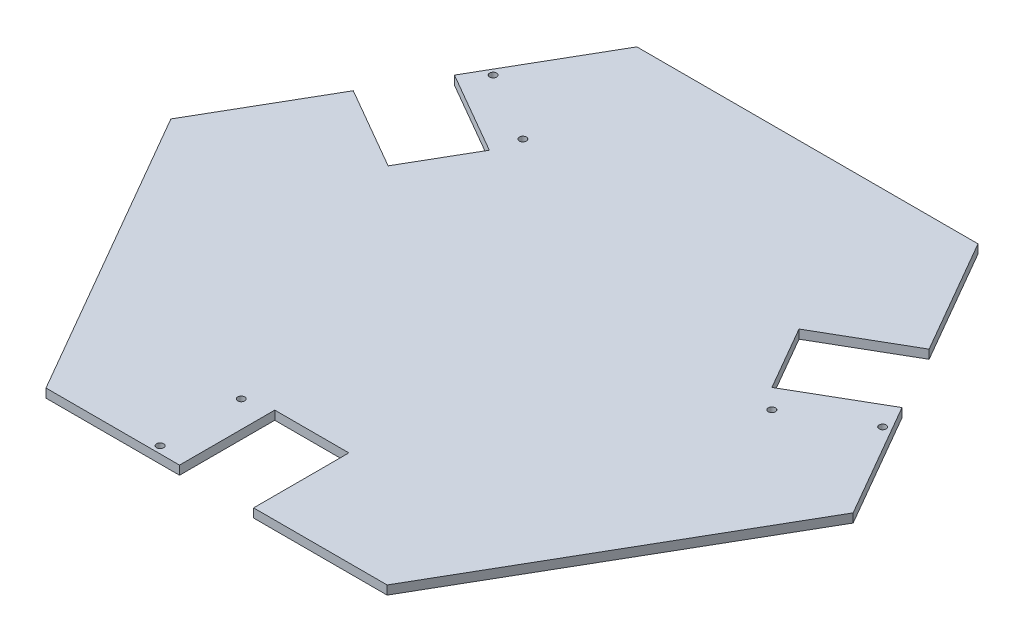
SolidWorks part; units mm, degrees
ref_plane "Front Plane" through (0, 0, 0) normal (0, 0, 1) x (1, 0, 0)
ref_plane "Top Plane" through (0, 0, 0) normal (0, 1, 0) x (1, 0, 0)
ref_plane "Right Plane" through (0, 0, 0) normal (1, 0, 0) x (0, 0, -1)
sketch "Sketch1" plane through (0, 0, 0) normal (0, 1, 0) x (1, 0, 0)
  line L0 (98.2939, 56.75) -> (0, 0) construction
  line L1 (-96.7062, 167.5) -> (-134.5593, 101.9365)
  line L2 (-96.7062, -167.5) -> (-21, -167.5)
  line L3 (193.4123, 0) -> (155.5593, 65.5635)
  line L4 (0, 0) -> (-145.0593, 83.75) construction
  line L5 (0, 0) -> (0, -167.5) construction
  line L6 (134.5593, 101.9365) -> (87.7939, 74.9365)
  line L7 (87.7939, 74.9365) -> (108.7939, 38.5635)
  line L8 (108.7939, 38.5635) -> (155.5593, 65.5635)
  line L9 (-108.7939, 38.5635) -> (-155.5593, 65.5635)
  line L10 (-87.7939, 74.9365) -> (-108.7939, 38.5635)
  line L11 (-134.5593, 101.9365) -> (-87.7939, 74.9365)
  line L12 (-21, -167.5) -> (-21, -113.5)
  line L13 (-21, -113.5) -> (21, -113.5)
  line L14 (21, -113.5) -> (21, -167.5)
  line L15 (-155.5593, 65.5635) -> (-193.4123, 0)
  line L16 (134.5593, 101.9365) -> (96.7062, 167.5)
  line L17 (21, -167.5) -> (96.7062, -167.5)
  line L18 (-96.7062, 167.5) -> (96.7062, 167.5)
  line L19 (96.7062, -167.5) -> (193.4123, 0)
  line L20 (-193.4123, 0) -> (-96.7062, -167.5)
  line L21 (-36, -117.5) -> (-36, -163.5) construction
  line L22 (-83.758, 89.9269) -> (-123.5952, 112.9269) construction
  line L23 (159.5952, 50.5731) -> (119.758, 27.5731) construction
  line L24 (-111.1766, 88.4365) -> (-94.889, 116.6475) construction
  line L25 (132.1766, 52.0635) -> (145.802, 28.4635) construction
  line L26 (-21, -140.5) -> (-46.048, -140.5) construction
  circle A0 centre (0, 0) radius 167.5 construction
  circle A1 centre (-36, -163.5) radius 2
  circle A2 centre (-36, -117.5) radius 2
  circle A3 centre (-123.5952, 112.9269) radius 2
  circle A4 centre (-83.758, 89.9269) radius 2
  circle A5 centre (159.5952, 50.5731) radius 2
  circle A6 centre (119.758, 27.5731) radius 2
  point P36 (86.6025, 50)
  point P37 (0, -150.4)
  point P38 (-86.6025, 50)
  point P39 (-111.1766, 88.4365)
  dimension "D1" = 335
  dimension "D13" = 4
  dimension "D14" = 15
  dimension "D15" = 46
  dimension "D16" = 15
  dimension "D18" = 46
  dimension "D19" = 4
  dimension "D7" = 23
  dimension "D2" = 54
  dimension "D3" = 21
  dimension "D4" = 21
  dimension "D5" = 21
  dimension "D6" = 120
  dimension "D8" = 23
  dimension "D9" = 23
  dimension "D20" = 15
  dimension "D22" = 46
  dimension "D23" = 100
  dimension "D24" = 100
  dimension "D26" = 17.1
extrude "Boss-Extrude1" add sketch "Sketch1" along normal blind 5
